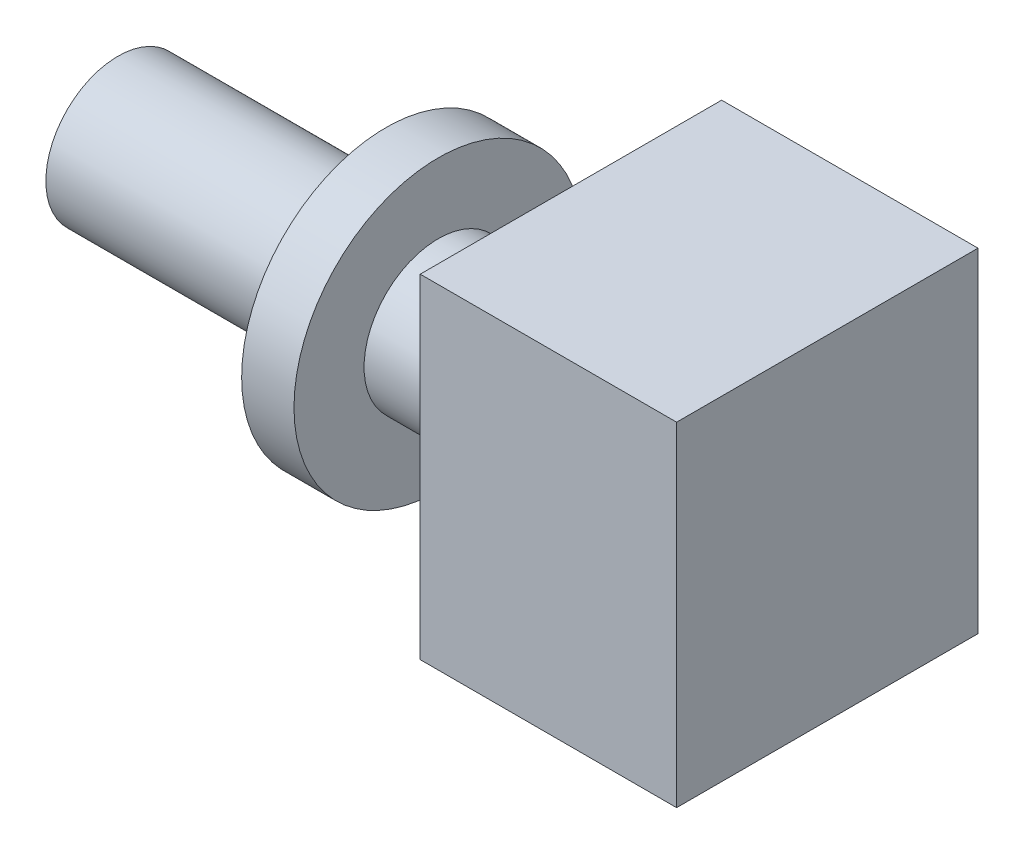
SolidWorks part; units mm, degrees
ref_plane "Front Plane" through (0, 0, 0) normal (0, 0, 1) x (1, 0, 0)
ref_plane "Top Plane" through (0, 0, 0) normal (0, 1, 0) x (1, 0, 0)
ref_plane "Right Plane" through (0, 0, 0) normal (1, 0, 0) x (0, 0, -1)
sketch "Sketch1" plane through (0, 0, 0) normal (1, 0, 0) x (0, 0, -1)
  circle A0 centre (0, 0) radius 17.5
extrude "Boss-Extrude1" add sketch "Sketch1" against normal blind 65
sketch "Sketch2" plane through (0, 0, 0) normal (1, 0, 0) x (0, 0, -1)
  circle A0 centre (0, 0) radius 35
extrude "Boss-Extrude2" add sketch "Sketch2" along normal blind 12.7
sketch "Sketch3" plane through (12.7, 0, 0) normal (1, 0, 0) x (0, 0, -1)
  circle A0 centre (0, 0) radius 18
extrude "Boss-Extrude3" add sketch "Sketch3" along normal blind 31.6
ref_plane "Plane1" through (44.3, 0, 0) normal (1, 0, 0) x (0, 0, -1)
sketch "Sketch4" plane through (44.3, 0, 0) normal (1, 0, 0) x (0, 0, -1)
  line L0 (-35.9729, -36.6709) -> (37.1541, -36.6709)
  line L1 (37.1541, -36.6709) -> (37.1541, 44.3291)
  line L2 (37.1541, 44.3291) -> (-35.9729, 44.3291)
  line L3 (-35.9729, 44.3291) -> (-35.9729, -36.6709)
extrude "Boss-Extrude4" add sketch "Sketch4" along normal blind 62.2
